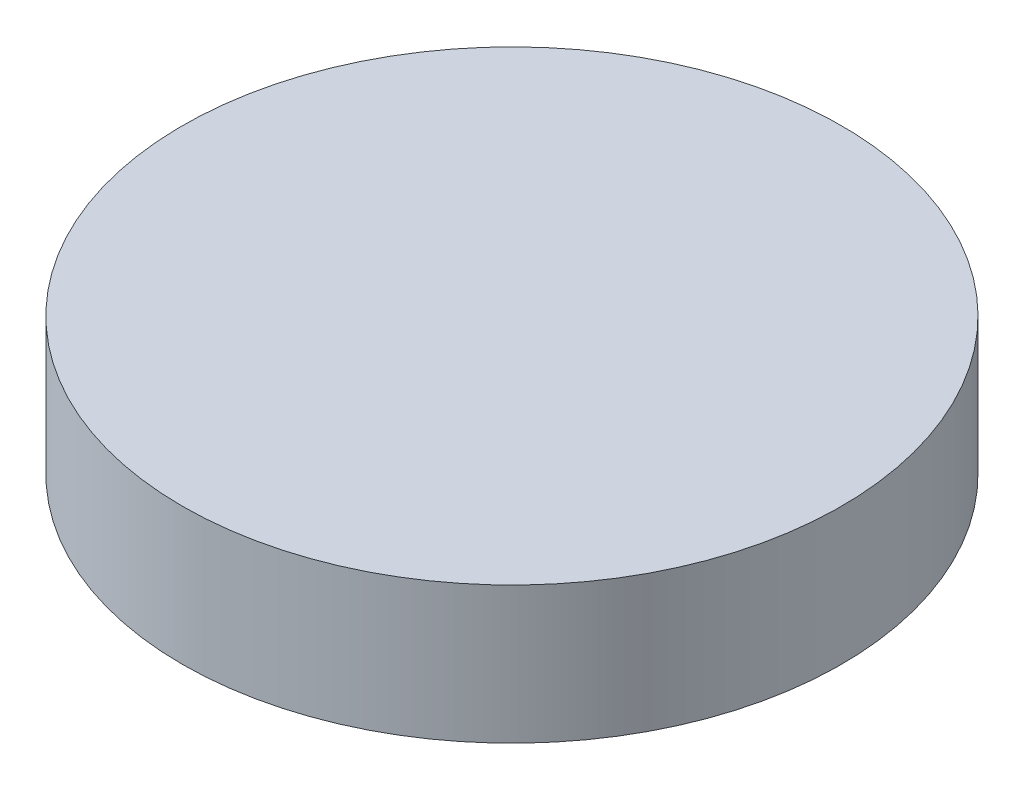
SolidWorks part; units mm, degrees
ref_plane "Front" through (0, 0, 0) normal (0, 0, 1) x (1, 0, 0)
ref_plane "Top" through (0, 0, 0) normal (0, 1, 0) x (1, 0, 0)
ref_plane "Right" through (0, 0, 0) normal (1, 0, 0) x (0, 0, -1)
sketch "Sketch1" plane through (0, 0, 0) normal (0, 1, 0) x (1, 0, 0)
  circle A0 centre (-0.4484, 0.6177) radius 16.5
extrude "Boss-Extrude1" add sketch "Sketch1" along normal blind 6.858
